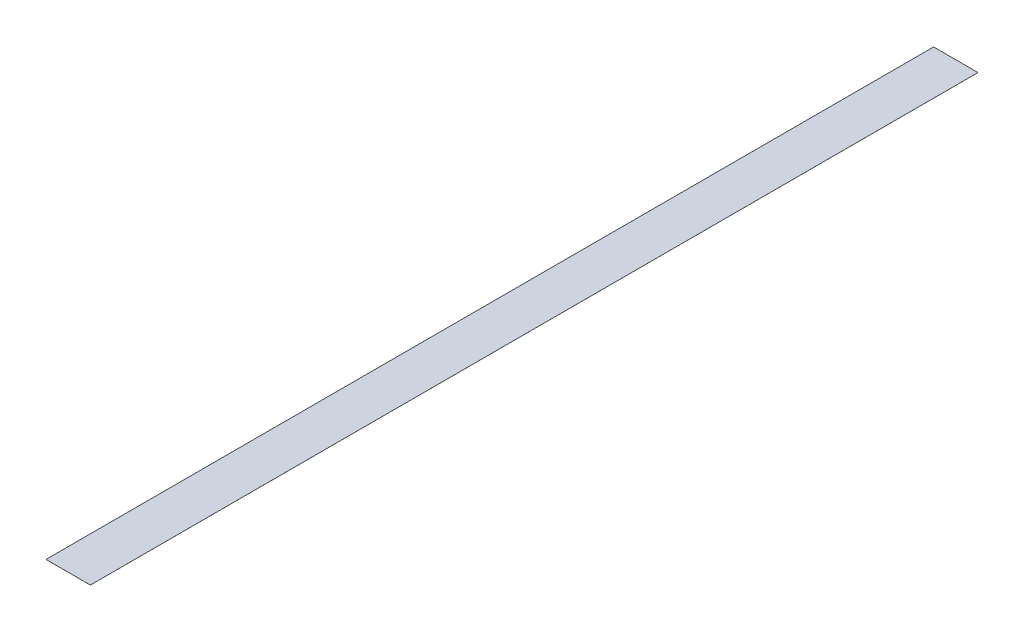
SolidWorks part; units mm, degrees
ref_plane "Plano frontal" through (0, 0, 0) normal (0, 0, 1) x (1, 0, 0)
ref_plane "Plano superior" through (0, 0, 0) normal (0, 1, 0) x (1, 0, 0)
ref_plane "Plano direito" through (0, 0, 0) normal (1, 0, 0) x (0, 0, -1)
sketch "Esboço1" plane through (0, 0, 0) normal (0, 1, 0) x (1, 0, 0)
  line L0 (-1093, 595.536) -> (-1073, 595.536)
  line L1 (0, 0) -> (18.9344, 0)
  line L2 (0, 0) -> (0, 766.8662)
  line L3 (0, 766.8662) -> (18.9344, 766.8662)
  line L4 (18.9344, 0) -> (18.9344, 766.8662)
  line L5 (-381.6968, 766.8662) -> (-362.7624, 766.8662)
  line L6 (-381.6968, 766.8662) -> (-381.6968, 345.536)
  line L7 (-381.6968, 345.536) -> (-362.7624, 345.536)
  line L8 (-362.7624, 766.8662) -> (-362.7624, 345.536)
  line L9 (-858.9344, 645.536) -> (-840, 645.536)
  line L10 (-858.9344, 645.536) -> (-858.9344, 345.536)
  line L11 (-858.9344, 345.536) -> (-840, 345.536)
  line L12 (-840, 645.536) -> (-840, 345.536)
  line L13 (-853.5858, 925.2213) -> (-1253.5858, 925.2213)
  line L14 (-853.5858, 925.2213) -> (-853.5858, 945.2213)
  line L15 (-853.5858, 945.2213) -> (-1253.5858, 945.2213)
  line L16 (-1253.5858, 925.2213) -> (-1253.5858, 945.2213)
  line L17 (-1093, 595.536) -> (-1093, 195.536)
  line L18 (-1093, 195.536) -> (-1073, 195.536)
  line L19 (-1073, 595.536) -> (-1073, 195.536)
  line L21 (-858.9344, 427.7897) -> (-1250.0103, 427.7897)
  line L23 (-858.9344, 407.7897) -> (-1250.0103, 407.7897)
  line L24 (-1250.0103, 427.7897) -> (-1250.0103, 407.7897)
  line L33 (-1439.6613, 239.7512) -> (-1560.0448, 239.7512)
  line L34 (-1439.6613, 239.7512) -> (-1439.6613, 219.7512)
  line L35 (-1439.6613, 219.7512) -> (-1560.0448, 219.7512)
  line L36 (-1560.0448, 239.7512) -> (-1560.0448, 219.7512)
  line L37 (-1627.2015, 576.144) -> (-1607.2015, 576.144)
  line L38 (-1627.2015, 576.144) -> (-1627.2015, 317.0654)
  line L39 (-1627.2015, 317.0654) -> (-1607.2015, 317.0654)
  line L40 (-1607.2015, 576.144) -> (-1607.2015, 317.0654)
  line L41 (-1627.2015, 769.6927) -> (-1607.2015, 769.6927)
  line L42 (-1627.2015, 769.6927) -> (-1627.2015, 1019.6927)
  line L43 (-1627.2015, 1019.6927) -> (-1607.2015, 1019.6927)
  line L44 (-1607.2015, 769.6927) -> (-1607.2015, 1019.6927)
  line L45 (382.1295, 902.6022) -> (402.1295, 902.6022)
  line L46 (382.1295, 902.6022) -> (382.1295, 502.6022)
  line L47 (382.1295, 502.6022) -> (402.1295, 502.6022)
  line L48 (402.1295, 902.6022) -> (402.1295, 502.6022)
  arc A6 (-381.6968, 766.8662) -> (18.9344, 766.8662) centre (-181.3812, 766.8662) cw
  arc A7 (-362.7624, 766.8662) -> (0, 766.8662) centre (-181.3812, 766.8662) cw
  arc A8 (-362.7624, 345.536) -> (-858.9344, 345.536) centre (-610.8484, 345.536) cw
  arc A9 (-381.6968, 345.536) -> (-840, 345.536) centre (-610.8484, 345.536) cw
  arc A10 (-840, 645.536) -> (-803.6955, 702.0415) centre (-777.8744, 645.536) cw
  arc A11 (-803.6955, 702.0415) -> (-853.5858, 945.2213) centre (-856.6336, 817.8884) ccw
  arc A12 (-858.9344, 645.536) -> (-814.4955, 717.9247) centre (-777.7563, 645.536) cw
  arc A13 (-814.4955, 717.9247) -> (-853.5858, 925.2213) centre (-864.2122, 815.8835) ccw
  arc A14 (-1093, 595.536) -> (-1188.5366, 677.9223) centre (-1176.2913, 595.536) ccw
  arc A15 (-1188.5366, 677.9223) -> (-1354.3411, 742.8189) centre (-1214.8489, 854.9525) cw
  arc A16 (-1354.3411, 742.8189) -> (-1253.5858, 945.2213) centre (-1257.3278, 820.805) cw
  arc A17 (-1073, 595.536) -> (-1188.5366, 698.0004) centre (-1176.2038, 595.536) ccw
  arc A18 (-1188.5366, 698.0004) -> (-1341.8208, 766.8662) centre (-1207.9995, 859.705) cw
  arc A19 (-1341.8208, 766.8662) -> (-1253.5858, 925.2213) centre (-1258.876, 824.4093) cw
  arc A22 (-1368.7558, 309.7722) -> (-1439.6613, 219.7512) centre (-1474.849, 320.402) cw
  arc A23 (-1388.5562, 309.7722) -> (-1439.6613, 239.7512) centre (-1477.6183, 321.1143) cw
  arc A24 (-1388.5562, 309.7722) -> (-1250.0103, 427.7897) centre (-1254.4723, 292.6965) cw
  arc A25 (-1607.2015, 317.0654) -> (-1560.0448, 239.7512) centre (-1520.2441, 317.0654) ccw
  arc A26 (-1627.2015, 317.0654) -> (-1560.0448, 219.7512) centre (-1523.1159, 317.0654) ccw
  arc A27 (-1368.7558, 309.7722) -> (-1250.0103, 407.7897) centre (-1259.9289, 298.8686) cw
extrude "Ressalto-extrusão13" add sketch "Esboço1" along normal blind 0.01 contours L48 L47 L46 L45
